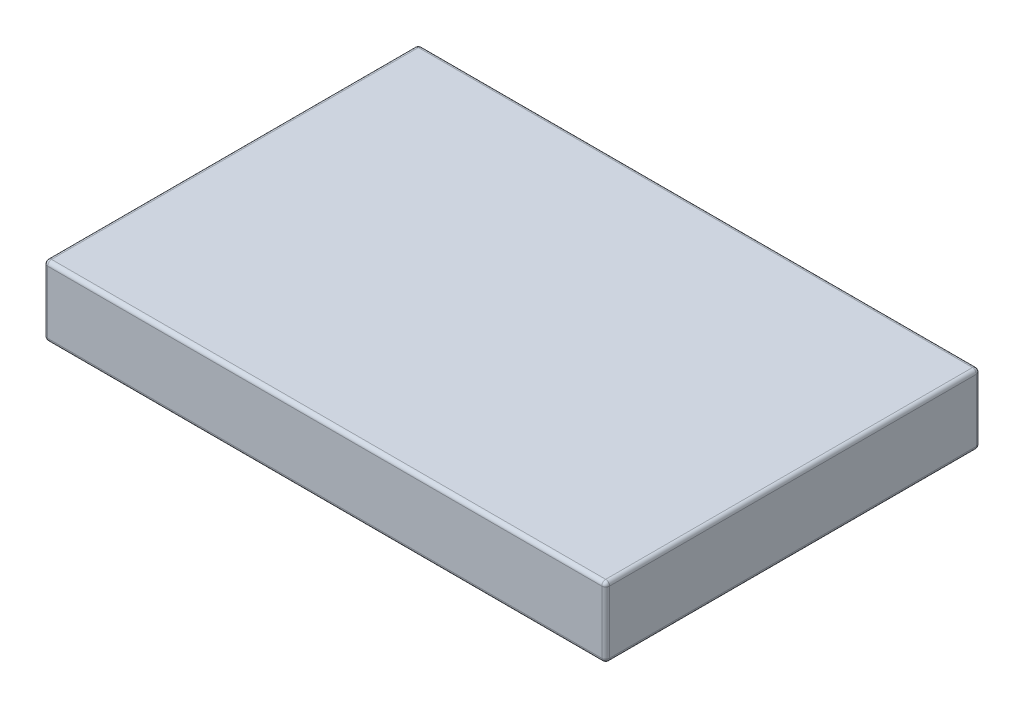
SolidWorks part; units mm, degrees
ref_plane "Front Plane" through (0, 0, 0) normal (0, 0, 1) x (1, 0, 0)
ref_plane "Top Plane" through (0, 0, 0) normal (0, 1, 0) x (1, 0, 0)
ref_plane "Right Plane" through (0, 0, 0) normal (1, 0, 0) x (0, 0, -1)
sketch "Sketch1" plane through (0, 0, 0) normal (0, 1, 0) x (1, 0, 0)
  line L1 (-1828.8, -1219.2) -> (1828.8, -1219.2)
  line L2 (-1828.8, -1219.2) -> (-1828.8, 1219.2)
  line L3 (-1828.8, 1219.2) -> (1828.8, 1219.2)
  line L4 (1828.8, -1219.2) -> (1828.8, 1219.2)
  line L5 (-1828.8, -1219.2) -> (1828.8, 1219.2) construction
  line L6 (-1828.8, 1219.2) -> (1828.8, -1219.2) construction
  point P0 (0, 0)
  dimension "D1" = 3657.6
  dimension "D2" = 2438.4
extrude "Boss-Extrude1" add sketch "Sketch1" along normal blind 457.2
fillet "Fillet1" radius 25.4 12 edges at (-1828.8, 0, 0) (-1828.8, 228.6, -1219.2) (0, 0, -1219.2) (1828.8, 228.6, -1219.2) (1828.8, 0, 0) (1828.8, 228.6, 1219.2) (0, 0, 1219.2) (-1828.8, 228.6, 1219.2) (-1828.8, 457.2, 0) (0, 457.2, -1219.2) (1828.8, 457.2, 0) (0, 457.2, 1219.2)
